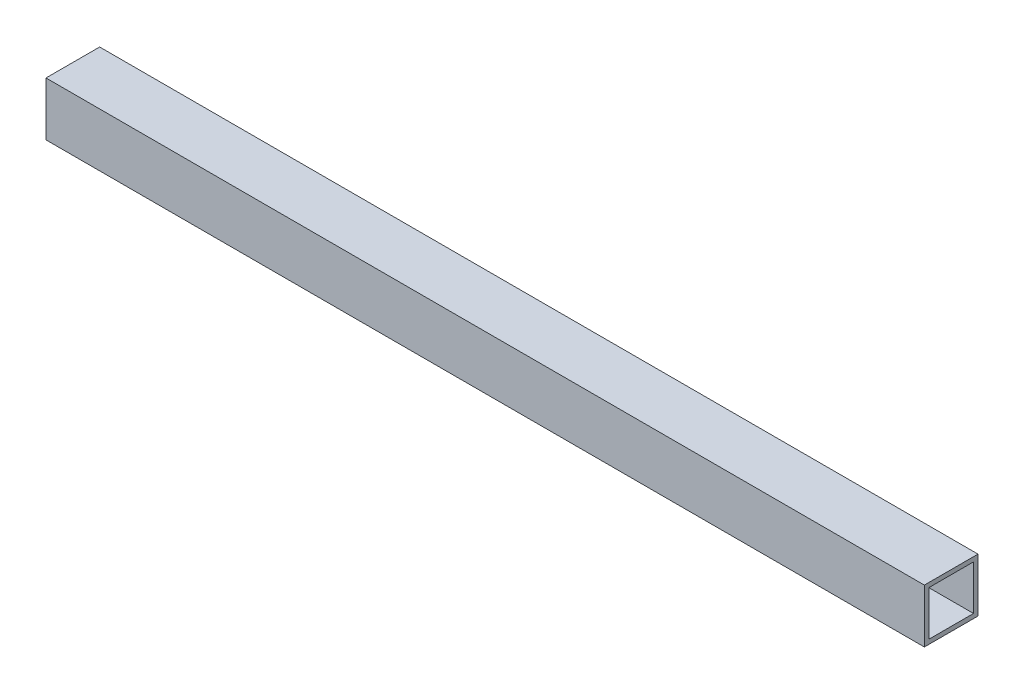
SolidWorks part; units mm, degrees
ref_plane "Front Plane" through (0, 0, 0) normal (0, 0, 1) x (1, 0, 0)
ref_plane "Top Plane" through (0, 0, 0) normal (0, 1, 0) x (1, 0, 0)
ref_plane "Right Plane" through (0, 0, 0) normal (1, 0, 0) x (0, 0, -1)
sketch "Sketch1" plane through (-983.1437, 0, 0) normal (1, 0, 0) x (0, 0, -1)
  line L0 (-768.0453, 79.306) -> (-768.0453, 63.431)
  line L1 (-769.6328, 80.8935) -> (-750.5828, 80.8935)
  line L2 (-769.6328, 80.8935) -> (-769.6328, 61.8435)
  line L3 (-769.6328, 61.8435) -> (-750.5828, 61.8435)
  line L4 (-750.5828, 80.8935) -> (-750.5828, 61.8435)
  line L5 (-768.0453, 63.431) -> (-752.1703, 63.431)
  line L6 (-752.1703, 79.306) -> (-752.1703, 63.431)
  line L7 (-768.0453, 79.306) -> (-752.1703, 79.306)
  line L8 (-370.0328, 80.8935) -> (-819.2328, 80.8935) construction
  line L9 (-594.6328, 87.8785) -> (-594.6328, 73.9085) construction
  dimension "D1" = 1.5875
  dimension "D2" = 19.05
  dimension "D3" = 175
extrude "Boss-Extrude1" add sketch "Sketch1" along normal up to surface (311.9 mm away)
ref_plane "Plane1" through (0, 0, 760.1078) normal (0, 0, 1) x (1, 0, 0)
